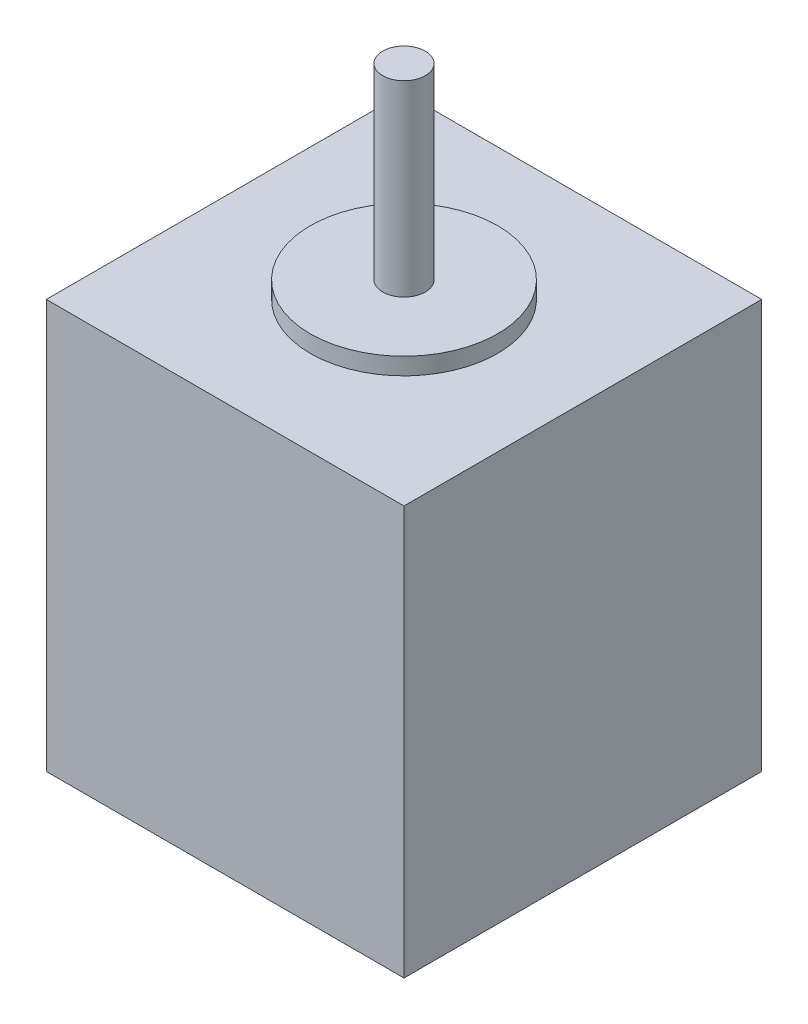
SolidWorks part; units mm, degrees
ref_plane "Front Plane" through (0, 0, 0) normal (0, 0, 1) x (1, 0, 0)
ref_plane "Top Plane" through (0, 0, 0) normal (0, 1, 0) x (1, 0, 0)
ref_plane "Right Plane" through (0, 0, 0) normal (1, 0, 0) x (0, 0, -1)
sketch "Sketch1" plane through (0, 0, 0) normal (0, 1, 0) x (1, 0, 0)
  line L0 (-21, 0) -> (21, 0) construction
  line L1 (-21, 21) -> (21, 21)
  line L2 (-21, 21) -> (-21, -21)
  line L3 (-21, -21) -> (21, -21)
  line L4 (21, 21) -> (21, -21)
  line L5 (-21, 21) -> (21, -21) construction
  line L6 (-21, -21) -> (21, 21) construction
  line L7 (-17.0799, 15.5799) -> (-14.0799, 15.5799) construction
  circle A0 centre (-15.5799, 15.5799) radius 1.5
  circle A1 centre (15.4196, 15.4196) radius 1.5
  circle A2 centre (15.4196, -15.4196) radius 1.5
  circle A3 centre (-15.5799, -15.5799) radius 1.5
  point P0 (0, 0)
  point P18 (0, 0)
  dimension "D3" = 3
  dimension "D4" = 3
  dimension "D5" = 31
  dimension "D1" = 42
  dimension "D2" = 42
extrude "Boss-Extrude2" add sketch "Sketch1" against normal blind 48 contours L2 L1 L4 L3
sketch "Sketch5" plane through (0, 0, 0) normal (0, 1, 0) x (1, 0, 0)
  circle A0 centre (0, 0) radius 11
  dimension "D1" = 22
extrude "Boss-Extrude3" add sketch "Sketch5" along normal blind 2
sketch "Sketch6" plane through (0, 2, 0) normal (0, 1, 0) x (1, 0, 0)
  circle A0 centre (0, 0) radius 2.5
  dimension "D1" = 5
extrude "Boss-Extrude4" add sketch "Sketch6" along normal blind 22
